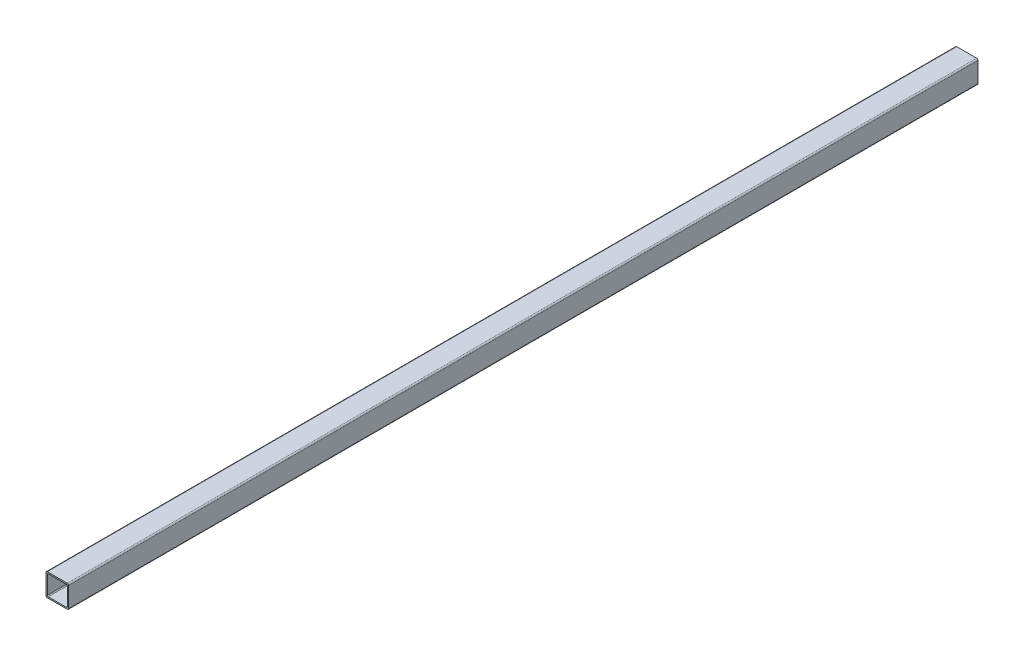
SolidWorks part; units mm, degrees
material "AISI 1020"
ref_plane "Спереди" through (0, 0, 0) normal (0, 0, 1) x (1, 0, 0)
ref_plane "Сверху" through (0, 0, 0) normal (0, 1, 0) x (1, 0, 0)
ref_plane "Справа" through (0, 0, 0) normal (1, 0, 0) x (0, 0, -1)
sketch "Эскиз1" plane through (0, 0, 0) normal (0, 0, 1) x (1, 0, 0)
  line L0 (-900, 0) -> (1525, 0) construction
  line B0 (6, 100) -> (94, 100)
  line B1 (0, 94) -> (0, 6)
  line B2 (6, 0) -> (94, 0)
  line B3 (100, 94) -> (100, 6)
  line B4 (10, 94) -> (90, 94)
  line B5 (6, 90) -> (6, 10)
  line B6 (10, 6) -> (90, 6)
  line B7 (94, 90) -> (94, 10)
  arc B8 (0, 6) -> (6, 0) centre (6, 6) ccw
  arc B9 (94, 0) -> (100, 6) centre (94, 6) ccw
  arc B10 (94, 100) -> (100, 94) centre (94, 94) cw
  arc B11 (6, 100) -> (0, 94) centre (6, 94) ccw
  arc B12 (6, 10) -> (10, 6) centre (10, 10) ccw
  arc B13 (90, 6) -> (94, 10) centre (90, 10) ccw
  arc B14 (90, 94) -> (94, 90) centre (90, 90) cw
  arc B15 (10, 94) -> (6, 90) centre (10, 90) ccw
sketch_block_instance "Пр_тр_100х100х6-1"
sketch_block "Пр_тр_100х100х6" parameters "D3"=6, "D4"=4, "D1"=100, "D2"=6
extrude "Бобышка-Вытянуть1" add sketch "Эскиз1" along normal up to surface (4020.283 mm away)
ref_plane "Плоскость1" through (50, 0, 0) normal (-1, 0, 0) x (0, 0, 1)
